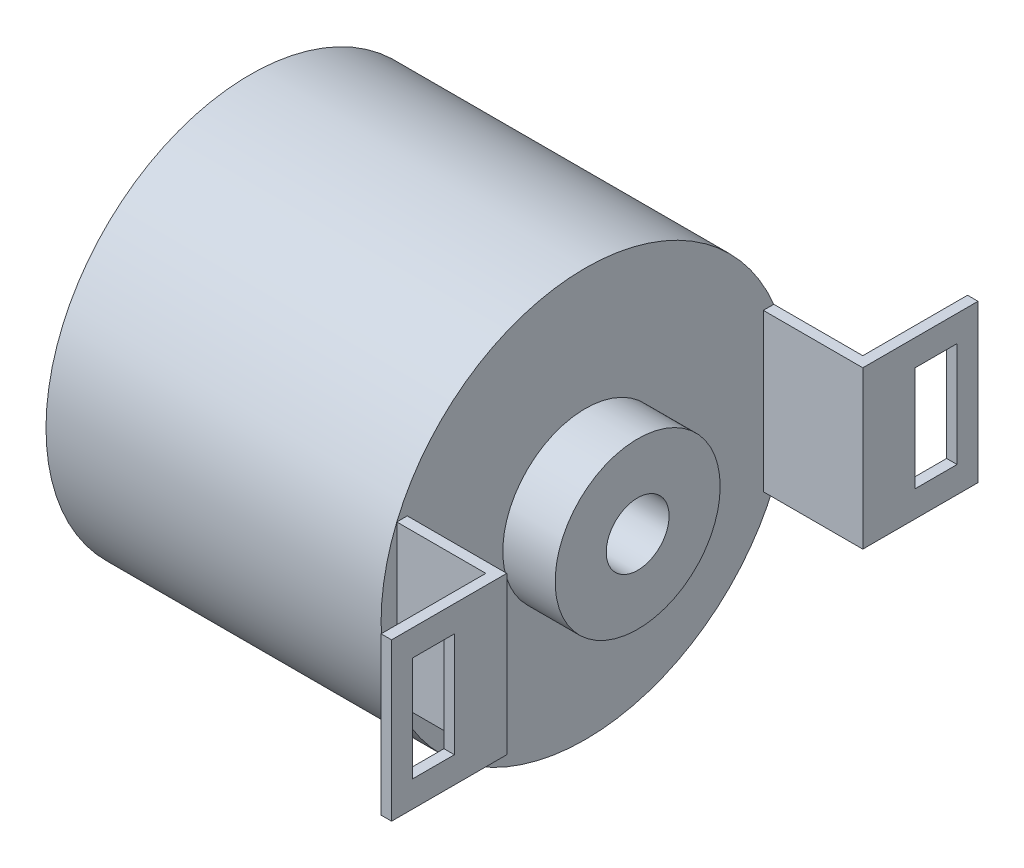
SolidWorks part; units mm, degrees
ref_plane "前视基准面" through (0, 0, 0) normal (0, 0, 1) x (1, 0, 0)
ref_plane "上视基准面" through (0, 0, 0) normal (0, 1, 0) x (1, 0, 0)
ref_plane "右视基准面" through (0, 0, 0) normal (1, 0, 0) x (0, 0, -1)
other "Configuration Table"
sketch "草图1" plane through (0, 0, 0) normal (1, 0, 0) x (0, 0, -1)
  circle A0 centre (0, 0) radius 19.5
  dimension "D1" = 39
extrude "凸台-拉伸1" add sketch "草图1" along normal blind 32
sketch "草图2" plane through (32, 0, 0) normal (1, 0, 0) x (0, 0, -1)
  circle A0 centre (0, 0) radius 7.88
  dimension "D1" = 15.76
extrude "凸台-拉伸2" add sketch "草图2" along normal blind 5
sketch "草图3" plane through (37, 0, 0) normal (1, 0, 0) x (0, 0, -1)
  circle A0 centre (0, 0) radius 3
  dimension "D1" = 6
extrude "切除-拉伸1" cut sketch "草图3" against normal up to next
sketch "草图4" plane through (32, 0, 0) normal (1, 0, 0) x (0, 0, -1)
  line L0 (0, 0) -> (19.5, 0) construction
  line L1 (0, 0) -> (-19.5, 0) construction
  line L2 (18, 7.5) -> (18, -7.5)
  line L3 (18, -7.5) -> (17, -7.5)
  line L4 (17, -7.5) -> (17, 7.5)
  line L5 (17, 7.5) -> (18, 7.5)
  circle A0 centre (0, 0) radius 19.5 construction
  dimension "D1" = 7.5
  dimension "D2" = 1
extrude "凸台-拉伸3" add sketch "草图4" along normal blind 9.5
sketch "草图6" plane through (0, 0, -18) normal (0, 0, -1) x (-1, 0, 0)
  line L0 (-41.5, -7.5) -> (-32, -7.5) construction
  line L1 (-41.5, 7.5) -> (-40.5, 7.5)
  line L2 (-41.5, 7.5) -> (-41.5, -7.5)
  line L3 (-41.5, -7.5) -> (-40.5, -7.5)
  line L4 (-40.5, 7.5) -> (-40.5, -7.5)
  dimension "D1" = 1
extrude "凸台-拉伸4" add sketch "草图6" along normal blind 10
sketch "草图7" plane through (41.5, 0, 0) normal (1, 0, 0) x (0, 0, -1)
  line L0 (28, 7.5) -> (17, 7.5) construction
  line L1 (22, 5) -> (26, 5)
  line L2 (22, 5) -> (22, -5)
  line L3 (22, -5) -> (26, -5)
  line L4 (26, 5) -> (26, -5)
  line L6 (28, 7.5) -> (28, -7.5) construction
  dimension "D1" = 10
  dimension "D2" = 2.5
  dimension "D3" = 4
  dimension "D4" = 2
extrude "切除-拉伸2" cut sketch "草图7" against normal blind 10
mirror "镜向1" about plane through (0, 0, 0) normal (0, 0, 1) of "凸台-拉伸3", "切除-拉伸2", "凸台-拉伸4"
